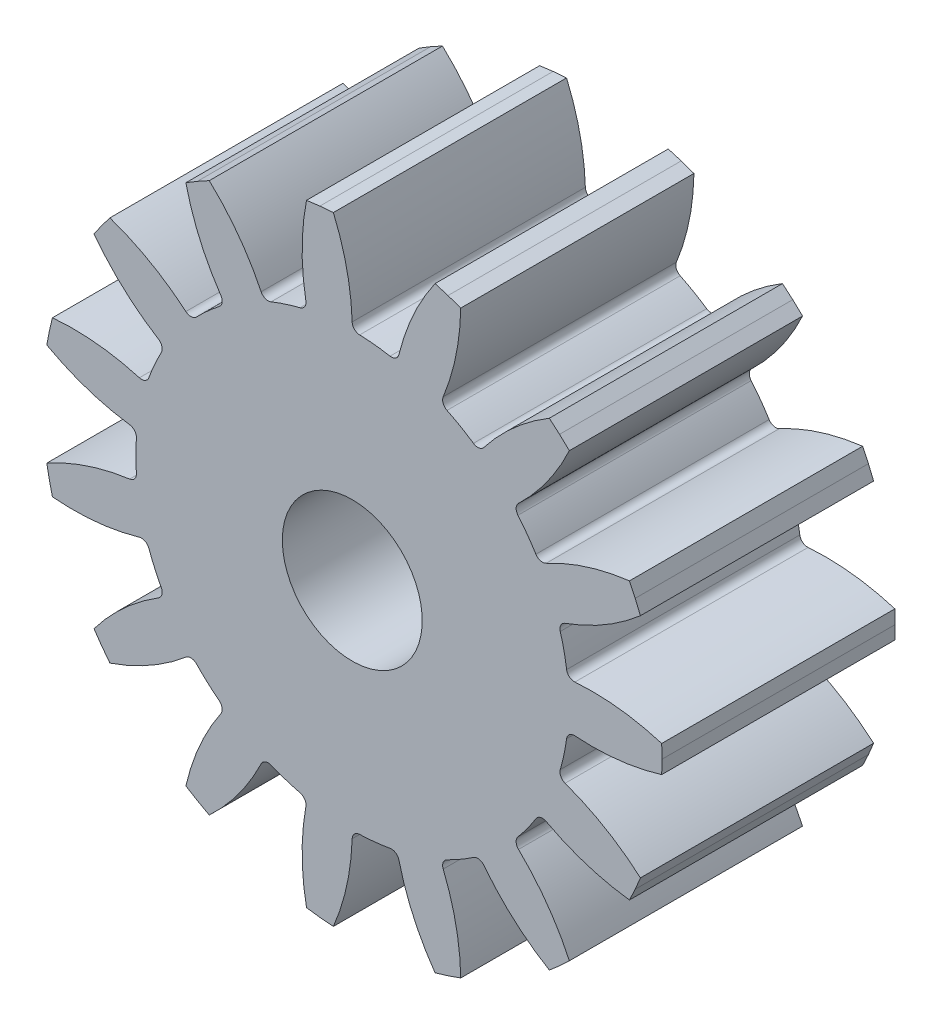
SolidWorks part; units mm, degrees
ref_plane "Front Plane" through (0, 0, 0) normal (0, 0, 1) x (1, 0, 0)
ref_plane "Top Plane" through (0, 0, 0) normal (0, 1, 0) x (1, 0, 0)
ref_plane "Right Plane" through (0, 0, 0) normal (1, 0, 0) x (0, 0, -1)
sketch "Sketch1" plane through (0, 0, 0) normal (0, 0, 1) x (1, 0, 0)
  line L0 (0, 0) -> (74.4139, 0) construction
  line L1 (0, 0) -> (9.0784, 1.9297) construction
  line L2 (0, 0) -> (74.4139, 7.8212) construction
  line L3 (0, 0) -> (74.4139, 3.249) construction
  line L4 (13.2686, 0.5793) -> (13.2812, 0)
  line L5 (0, 0) -> (9.0784, -1.9297) construction
  line L6 (0, 0) -> (9.0784, 1.9297)
  line L7 (0, 0) -> (9.0784, -1.9297) construction
  line L8 (0, 0) -> (9.0784, -1.9297)
  line L9 (13.2686, -0.5793) -> (13.2812, 0)
  circle A0 centre (0, 0) radius 13.2812 construction
  circle A1 centre (0, 0) radius 11.7188 construction
  circle A2 centre (0, 0) radius 9.2812 construction
  arc A3 (9.2304, 0.9702) -> (13.2686, 0.5793) centre (10.2914, -9.1246) cw
  arc A4 (9.2304, 0.9702) -> (9.0784, 1.9297) centre (0, 0) ccw
  arc A5 (9.2304, -0.9702) -> (9.0784, -1.9297) centre (0, 0) cw
  arc A6 (9.2304, -0.9702) -> (13.2686, -0.5793) centre (10.2914, 9.1246) ccw
  dimension "D1" = 26.5625
  dimension "D2" = 1.5625
  dimension "D3" = 2.4375
  dimension "D4" = 12
  dimension "D5" = 6
  dimension "D6" = 2.5
extrude "Boss-Extrude1" add sketch "Sketch1" along normal blind 10
fillet "Fillet1" radius 0.3325 2 edges at (9.2304, 0.9702, 5) (9.2304, -0.9702, 5)
pattern_circular "CirPattern1" count 15 over 360 about axis through (0, 0, 0) along (0, 0, 1) of "Boss-Extrude1", "Fillet1"
sketch "Sketch2" plane through (0, 0, 0) normal (0, 0, -1) x (-1, 0, 0)
  circle A0 centre (0, 0) radius 3
  dimension "D1" = 6
extrude "Cut-Extrude1" cut sketch "Sketch2" against normal up to next
